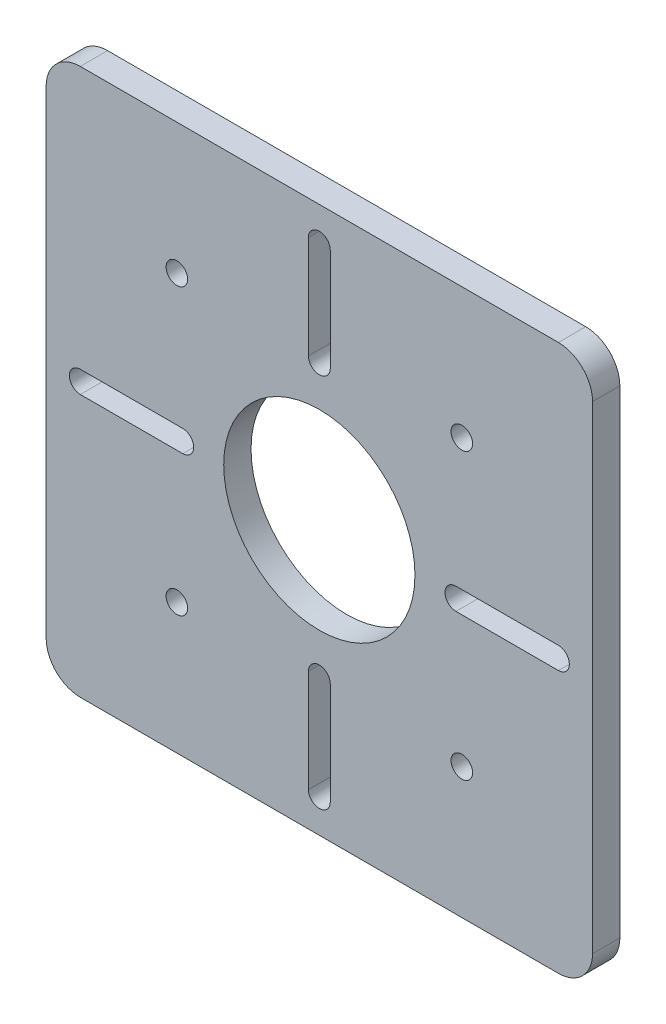
SolidWorks part; units mm, degrees
ref_plane "Front Plane" through (0, 0, 0) normal (0, 0, 1) x (1, 0, 0)
ref_plane "Top Plane" through (0, 0, 0) normal (0, 1, 0) x (1, 0, 0)
ref_plane "Right Plane" through (0, 0, 0) normal (1, 0, 0) x (0, 0, -1)
sketch "Sketch2" plane through (0, 0, 0) normal (0, 0, 1) x (1, 0, 0)
  line L0 (1.6, 20) -> (1.6, 35)
  line L1 (-1.6, 35) -> (-1.6, 20)
  line L2 (1.6, -35) -> (1.6, -20)
  line L3 (-1.6, -20) -> (-1.6, -35)
  line L4 (20, -1.6) -> (35, -1.6)
  line L5 (35, 1.6) -> (20, 1.6)
  line L6 (-35, -1.6) -> (-20, -1.6)
  line L7 (-20, 1.6) -> (-35, 1.6)
  line L8 (-40, -40) -> (40, -40)
  line L9 (-40, -40) -> (-40, 40)
  line L10 (-40, 40) -> (40, 40)
  line L11 (40, -40) -> (40, 40)
  line L12 (-40, -40) -> (40, 40) construction
  line L13 (-40, 40) -> (40, -40) construction
  arc A0 (1.6, 35) -> (0, 36.6) centre (0, 35) ccw
  arc A1 (0, 36.6) -> (-1.6, 35) centre (0, 35) ccw
  arc A2 (-1.6, 20) -> (1.6, 20) centre (0, 20) ccw
  arc A3 (-1.6, -35) -> (1.6, -35) centre (0, -35) ccw
  arc A4 (1.6, -20) -> (0, -18.4) centre (0, -20) ccw
  arc A5 (0, -18.4) -> (-1.6, -20) centre (0, -20) ccw
  arc A6 (35, -1.6) -> (35, 1.6) centre (35, 0) ccw
  arc A7 (20, 1.6) -> (20, -1.6) centre (20, 0) ccw
  arc A8 (0, -14) -> (0, 14) centre (0, 0) ccw
  arc A9 (0, 14) -> (0, -14) centre (0, 0) ccw
  arc A10 (-20, -1.6) -> (-20, 1.6) centre (-20, 0) ccw
  arc A11 (-35, 1.6) -> (-35, -1.6) centre (-35, 0) ccw
  circle A12 centre (-20.8597, -20.8597) radius 1.575
  circle A13 centre (-20.8597, 20.8597) radius 1.575
  circle A14 centre (20.8597, 20.8597) radius 1.575
  circle A15 centre (20.8597, -20.8597) radius 1.575
  point P47 (0, 0)
  dimension "D2" = 3.15
  dimension "D1" = 80
  dimension "D3" = 29.5
  dimension "D4" = 4
extrude "Boss-Extrude1" add sketch "Sketch2" along normal blind 4
fillet "Fillet1" radius 5 4 edges at (-40, 40, 2) (40, 40, 2) (40, -40, 2) (-40, -40, 2)
